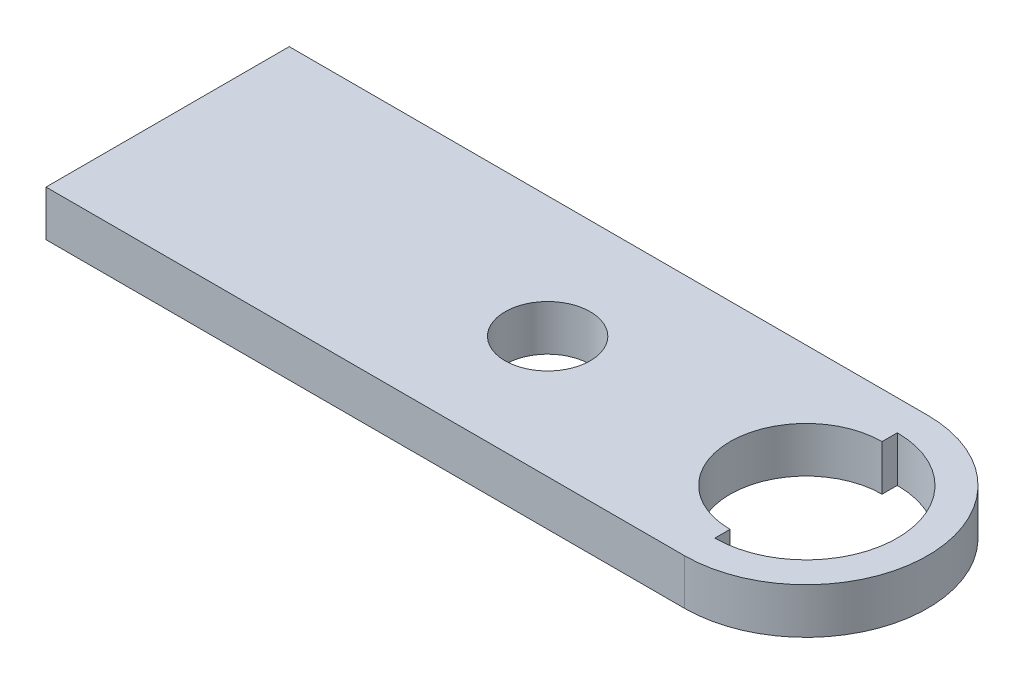
SolidWorks part; units mm, degrees
ref_plane "Front Plane" through (0, 0, 0) normal (0, 0, 1) x (1, 0, 0)
ref_plane "Top Plane" through (0, 0, 0) normal (0, 1, 0) x (1, 0, 0)
ref_plane "Right Plane" through (0, 0, 0) normal (1, 0, 0) x (0, 0, -1)
sketch "Sketch1" plane through (0, 0, 0) normal (0, 1, 0) x (1, 0, 0)
  line L0 (-140.4204, 0) -> (163.7022, 0) construction
  line L1 (-114.7769, 40) -> (95.2231, 40)
  line L2 (-114.7769, 40) -> (-114.7769, -40)
  line L3 (-114.7769, -40) -> (95.2231, -40)
  line L5 (95.2231, 30) -> (95.2231, 25)
  line L6 (95.2231, -25) -> (95.2231, -30)
  line L7 (0, -52.1085) -> (0, 59.281) construction
  arc A0 (95.2231, -40) -> (95.2231, 40) centre (95.2231, 0) ccw
  arc A1 (95.2231, -30) -> (95.2231, 30) centre (95.2231, 0) ccw
  arc A2 (95.2231, 25) -> (95.2231, -25) centre (95.2231, 0) ccw
  point P0 (0, 0)
  dimension "D3" = 210
  dimension "D2" = 40
  dimension "D4" = 60
  dimension "D5" = 50
  dimension "D1" = 80
extrude "Boss-Extrude1" add sketch "Sketch1" along normal blind 15
hole_wizard "Tap Drill for M30x2.0 Tap1" positions "Sketch3" profile "Sketch4" hole size "M30x2.0" standard "ANSI Metric" end condition through all
sketch "Sketch3" plane through (0, 15, 0) normal (0, 1, 0) x (1, 0, 0)
  line L0 (-29.516, 0) -> (28.305, 0) construction
  arc A0 (95.2231, 25) -> (95.2231, -25) centre (95.2231, 0) ccw construction
  point P0 (10.2231, 0)
  dimension "D1" = 85
sketch "Sketch4" plane through (10.2231, 15, 0) normal (1, 0, 0) x (0, 0, 1)
  line L0 (0, 0) -> (0, 15)
  line L1 (0, 15) -> (14, 15)
  line L2 (14, 15) -> (14, 0)
  line L5 (14, 0) -> (0, 0)
  line L11 (0, -6.35) -> (0, 107.95) construction
  dimension "Thru Hole Dia." = 28
  dimension "Thru Hole Depth" = 15
